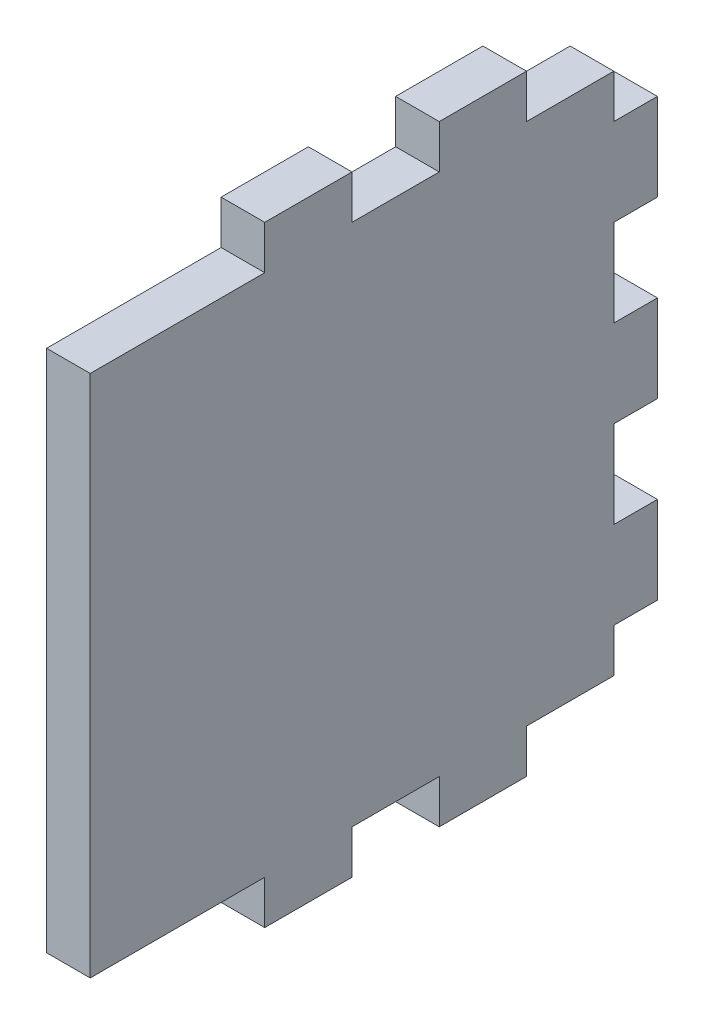
SolidWorks part; units mm, degrees
ref_plane "Front Plane" through (0, 0, 0) normal (1, 0, 0) x (0, 1, 0)
ref_plane "Top Plane" through (0, 0, 0) normal (0, 0, 1) x (0, 1, 0)
ref_plane "Right Plane" through (0, 0, 0) normal (0, 1, 0) x (-1, 0, 0)
sketch "Sketch1" plane through (0, 0, 0) normal (1, 0, 0) x (0, 1, 0)
  line L1 (0, 0) -> (88.9, 0)
  line L2 (0, 0) -> (0, 82.55)
  line L3 (0, 82.55) -> (88.9, 82.55)
  line L4 (88.9, 0) -> (88.9, 82.55)
  dimension "D1" = 88.9
  dimension "D2" = 82.55
extrude "Boss-Extrude1" add sketch "Sketch1" along normal blind 6.35
sketch "Sketch2" plane through (6.35, 0, 0) normal (1, 0, 0) x (0, 1, 0)
  line L5 (50.8, 0) -> (63.5, 0)
  line L23 (50.8, 0) -> (50.8, 6.35)
  line L48 (0, 0) -> (88.9, 0) construction
  line L49 (50.8, 6.35) -> (63.5, 6.35)
  line L50 (25.4, 0) -> (38.1, 0)
  line L51 (0, 0) -> (12.7, 0)
  line L52 (0, 0) -> (0, 6.35)
  line L53 (6.35, 6.35) -> (12.7, 6.35)
  line L54 (12.7, 0) -> (12.7, 6.35)
  line L55 (25.4, 0) -> (25.4, 6.35)
  line L56 (25.4, 6.35) -> (38.1, 6.35)
  line L57 (38.1, 0) -> (38.1, 6.35)
  line L58 (76.2, 0) -> (88.9, 0)
  line L59 (76.2, 0) -> (76.2, 6.35)
  line L60 (76.2, 6.35) -> (82.55, 6.35)
  line L61 (88.9, 0) -> (88.9, 6.35)
  line L62 (63.5, 0) -> (63.5, 6.35)
  line L63 (0, 82.55) -> (0, 0) construction
  line L64 (0, 82.55) -> (6.35, 82.55)
  line L65 (0, 82.55) -> (0, 57.15)
  line L66 (0, 57.15) -> (6.35, 57.15)
  line L67 (6.35, 82.55) -> (6.35, 57.15)
  line L68 (88.9, 82.55) -> (0, 82.55) construction
  line L70 (0, 44.45) -> (6.35, 44.45)
  line L71 (0, 44.45) -> (0, 31.75)
  line L72 (0, 31.75) -> (6.35, 31.75)
  line L73 (6.35, 44.45) -> (6.35, 31.75)
  line L86 (88.9, 6.35) -> (88.9, 19.05)
  line L87 (88.9, 19.05) -> (82.55, 19.05)
  line L88 (82.55, 44.45) -> (82.55, 31.75)
  line L89 (88.9, 31.75) -> (82.55, 31.75)
  line L90 (88.9, 44.45) -> (88.9, 31.75)
  line L91 (88.9, 44.45) -> (82.55, 44.45)
  line L92 (82.55, 82.55) -> (82.55, 57.15)
  line L93 (88.9, 57.15) -> (82.55, 57.15)
  line L94 (88.9, 82.55) -> (88.9, 57.15)
  line L95 (88.9, 82.55) -> (82.55, 82.55)
  line L96 (82.55, 6.35) -> (82.55, 19.05)
  line L98 (6.35, 6.35) -> (6.35, 19.05)
  line L99 (6.35, 19.05) -> (0, 19.05)
  line L100 (0, 6.35) -> (0, 19.05)
  dimension "D5" = 12.7
  dimension "D6" = 6.35
  dimension "D8" = 12.7
  dimension "D9" = 6.35
  dimension "D10" = 0
  dimension "D11" = 12.7
  dimension "D12" = 12.7
  dimension "D14" = 6.35
  dimension "D24" = 12.7
  dimension "D26" = 12.7
  dimension "D31" = 6.35
  dimension "1" = 25.4
extrude "Cut-Extrude2" cut sketch "Sketch2" against normal blind 6.35
